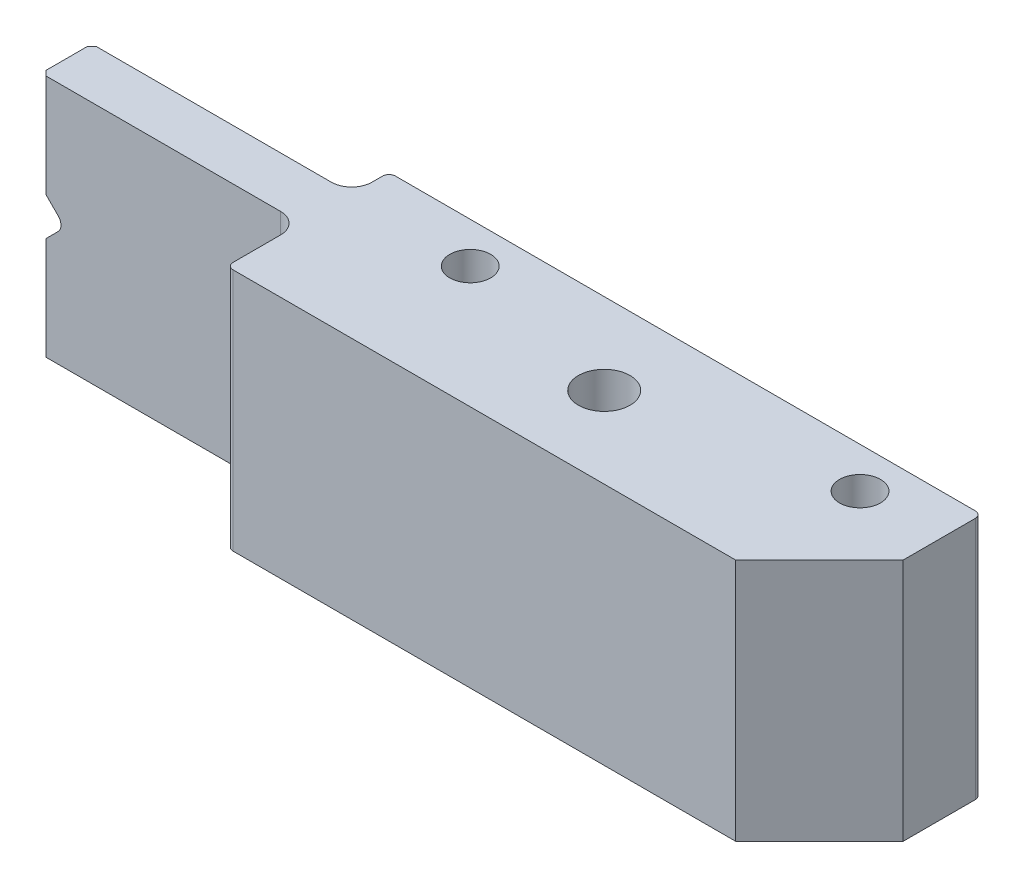
SolidWorks part; units mm, degrees
material "Acero M2"
ref_plane "Alzado" through (0, 0, 0) normal (0, 0, 1) x (1, 0, 0)
ref_plane "Planta" through (0, 0, 0) normal (0, 1, 0) x (1, 0, 0)
ref_plane "Vista lateral" through (0, 0, 0) normal (1, 0, 0) x (0, 0, -1)
sketch "Croquis1" plane through (0, 0, 0) normal (0, 0, 1) x (1, 0, 0)
  line L1 (0, 0) -> (66.675, 0)
  line L2 (0, 0) -> (0, -19.05)
  line L3 (0, -19.05) -> (66.675, -19.05)
  line L4 (66.675, 0) -> (66.675, -19.05)
  line L5 (33.3375, -19.05) -> (33.3375, 0) construction
  line L6 (0, -9.525) -> (66.675, -9.525) construction
  point P188 (33.3375, -9.525)
  dimension "D1" = 66.675
  dimension "D2" = 19.05
extrude "Saliente-Extruir1" add sketch "Croquis1" along normal blind 12.7
sketch "Croquis2" plane through (0, 0, 0) normal (0, 1, 0) x (1, 0, 0)
  line L1 (0, 0) -> (20.32, 0)
  line L2 (0, 0) -> (0, -2.921)
  line L3 (0, -2.921) -> (20.32, -2.921)
  line L4 (20.32, 0) -> (20.32, -2.921)
  line L5 (10.16, -2.921) -> (10.16, 0) construction
  line L6 (0, -1.4605) -> (20.32, -1.4605) construction
  line L7 (0, -12.7) -> (20.32, -12.7)
  line L8 (0, -12.7) -> (0, -6.8834)
  line L9 (0, -6.8834) -> (20.32, -6.8834)
  line L10 (20.32, -12.7) -> (20.32, -6.8834)
  line L11 (10.16, -6.8834) -> (10.16, -12.7) construction
  line L12 (0, -9.7917) -> (20.32, -9.7917) construction
  point P144 (10.16, -1.4605)
  point P182 (10.16, -9.7917)
  dimension "D1" = 20.32
  dimension "D2" = 2.921
  dimension "D3" = 3.9624
extrude "Cortar-Extruir1" cut sketch "Croquis2" against normal through all
fillet "Redondeo1" radius 1.5875 2 edges at (20.32, -9.525, 2.921) (20.32, -9.525, 6.8834)
hole_wizard "Taladros de espiga de 1/8 (0.126)1" positions "Croquis3" profile "Croquis4" hole size "1/8" standard "Ansi Inch" end condition through all
sketch "Croquis3" plane through (0, 0, 0) normal (0, 1, 0) x (1, 0, 0)
  line L0 (29.845, -3.175) -> (60.325, -3.175) construction
  line L2 (66.675, 0) -> (20.32, 0) construction
  line L3 (66.675, -12.7) -> (66.675, 0) construction
  point P0 (60.325, -3.175)
  point P2 (29.845, -3.175)
  dimension "D1" = 3.175
  dimension "D2" = 6.35
  dimension "D3" = 36.83
sketch "Croquis4" plane through (60.325, 0, 3.175) normal (1, 0, 0) x (0, 0, 1)
  line L0 (0, 0) -> (0, 19.05)
  line L1 (0, 19.05) -> (1.6002, 19.05)
  line L2 (1.6002, 19.05) -> (1.6002, 0)
  line L5 (1.6002, 0) -> (0, 0)
  line L11 (0, -6.35) -> (0, 107.95) construction
  dimension "Diámetro de taladro hasta el siguiente" = 3.2004
  dimension "Profundidad de taladro hasta el siguiente" = 19.05
hole_wizard "Taladro roscado #10-321" positions "Croquis5" profile "Croquis6" tap size "#10-32" standard "Ansi Inch" end condition through all
sketch "Croquis5" plane through (0, 0, 0) normal (0, 1, 0) x (1, 0, 0)
  line L0 (66.675, -12.7) -> (66.675, 0) construction
  line L1 (66.675, 0) -> (20.32, 0) construction
  point P0 (43.4975, -6.35)
  dimension "D1" = 23.1775
  dimension "D2" = 6.35
sketch "Croquis6" plane through (43.4975, 0, 6.35) normal (1, 0, 0) x (0, 0, 1)
  line L0 (0, 0) -> (0, 19.05)
  line L1 (0, 19.05) -> (2.0193, 19.05)
  line L2 (2.0193, 19.05) -> (2.0193, 0)
  line L5 (2.0193, 0) -> (0, 0)
  line L11 (0, -6.35) -> (0, 107.95) construction
  dimension "Diámetro de perforador para roscar hasta el siguiente" = 4.0386
  dimension "Profundidad de perforador para roscar hasta el siguiente" = 19.05
cosmetic thread "Rosca de taladro1" parameters "D2"=4.826
sketch "Croquis7" plane through (0, 0, 0) normal (0, 1, 0) x (1, 0, 0)
  line L0 (66.675, -6.1468) -> (60.1218, -12.7)
  line L1 (66.675, -12.7) -> (66.675, 0) construction
  line L2 (66.675, -12.7) -> (20.32, -12.7) construction
  line L3 (60.1218, -12.7) -> (66.675, -12.7)
  line L4 (66.675, -12.7) -> (66.675, -6.1468)
  dimension "D1" = 45
  dimension "D2" = 6.1468
extrude "Cortar-Extruir2" cut sketch "Croquis7" against normal through all
sketch "Croquis8" plane through (0, 0, 2.921) normal (0, 0, -1) x (-1, 0, 0)
  line L0 (0, -7.66) -> (-1.3262, -8.9862)
  line L1 (0, -19.05) -> (0, 0) construction
  line L2 (-1.3262, -10.0638) -> (0, -11.39)
  line L3 (0, -11.39) -> (0, -7.66)
  line L4 (-0.7874, -9.525) -> (0, -9.525) construction
  arc A0 (-1.3262, -10.0638) -> (-1.3262, -8.9862) centre (-0.7874, -9.525) cw
  point P10 (-1.5494, -9.525)
  point P18 (0, -9.525)
  dimension "D1" = 0.762
  dimension "D2" = 1.5494
  dimension "D3" = 90
extrude "Cortar-Extruir3" cut sketch "Croquis8" against normal through all
sketch "Croquis10" plane through (0, 0, 0) normal (0, 0, -1) x (-1, 0, 0)
  line L0 (-61.7021, -12.7) -> (-25.2929, -12.7) construction
  line L1 (-43.4975, -12.7) -> (-43.4975, -19.05) construction
  line L2 (-20.32, -19.05) -> (-66.675, -19.05) construction
  text T0 "MM 90-4150-06"
  dimension "D1" = 6.35
extrude "Cortar-Extruir4" cut sketch "Croquis10" against normal blind 0.381
fillet "Redondeo2" radius 0.508 3 edges at (66.675, -9.525, 0) (20.32, -9.525, 12.7) (20.32, -9.525, 0)
chamfer "Chaflán1" distance 0.381 angle 45 4 edges at (0, -15.22, 6.8834) (0, -15.22, 2.921) (0, -3.83, 6.8834) (0, -3.83, 2.921)
